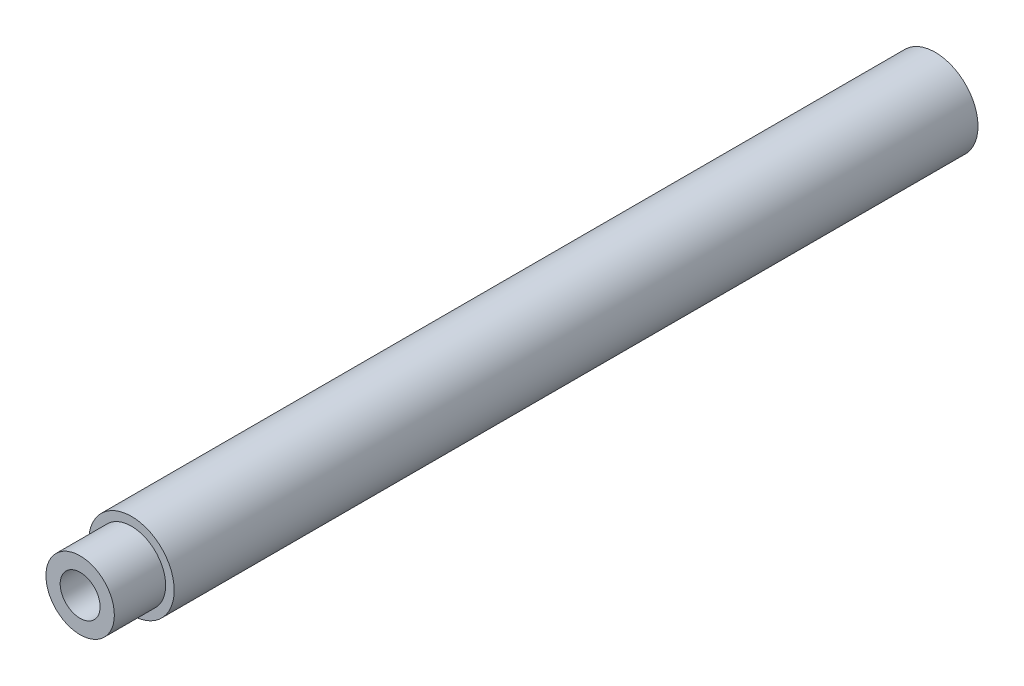
SolidWorks part; units mm, degrees
ref_plane "Front Plane" through (0, 0, 0) normal (0, 0, 1) x (1, 0, 0)
ref_plane "Top Plane" through (0, 0, 0) normal (0, 1, 0) x (1, 0, 0)
ref_plane "Right Plane" through (0, 0, 0) normal (1, 0, 0) x (0, 0, -1)
sketch "Sketch1" plane through (0, 0, 0) normal (0, 0, 1) x (1, 0, 0)
  circle A0 centre (0, 0) radius 7.5
  dimension "D1" = 15
extrude "Boss-Extrude1" add sketch "Sketch1" along normal blind 150
sketch "Sketch2" plane through (0, 0, 150) normal (0, 0, 1) x (1, 0, 0)
  circle A0 centre (0, 0) radius 7.5
  circle A1 centre (0, 0) radius 6
extrude "Cut-Extrude1" cut sketch "Sketch2" against normal blind 9
sketch "Sketch3" plane through (0, 0, 150) normal (0, 0, 1) x (1, 0, 0)
  circle A0 centre (0, 0) radius 3.5
extrude "Cut-Extrude2" cut sketch "Sketch3" against normal blind 20
